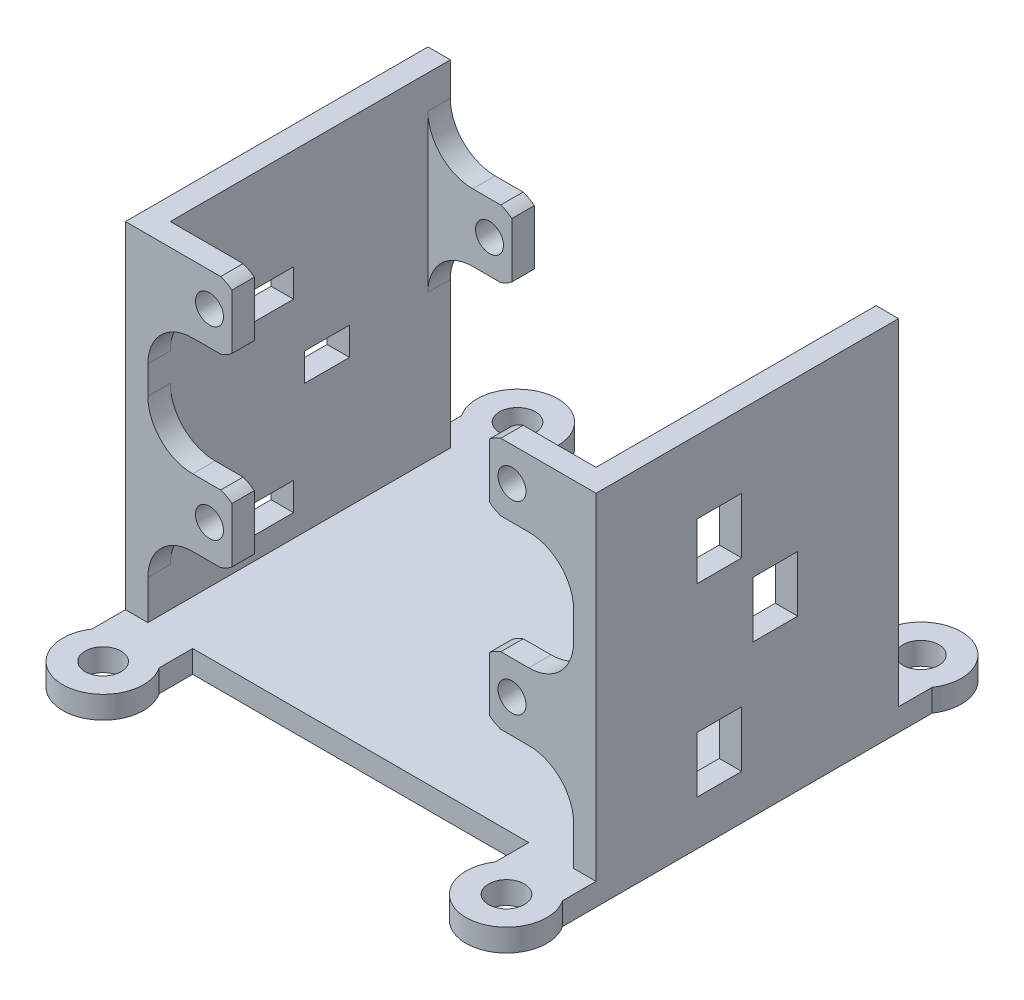
SolidWorks part; units mm, degrees
ref_plane "Спереди" through (0, 0, 0) normal (0, 0, 1) x (1, 0, 0)
ref_plane "Сверху" through (0, 0, 0) normal (0, 1, 0) x (1, 0, 0)
ref_plane "Справа" through (0, 0, 0) normal (1, 0, 0) x (0, 0, -1)
sketch "Эскиз1" plane through (0, 0, 0) normal (0, 1, 0) x (1, 0, 0)
  line L1 (21, -13.5) -> (-21, -13.5)
  line L2 (21, -13.5) -> (21, 13.5)
  line L3 (21, 13.5) -> (-21, 13.5)
  line L4 (-21, -13.5) -> (-21, 13.5)
  line L5 (21, -13.5) -> (-21, 13.5) construction
  line L6 (21, 13.5) -> (-21, -13.5) construction
  point P0 (0, 0)
  dimension "D1" = 42
  dimension "D2" = 27
extrude "Бобышка-Вытянуть1" add sketch "Эскиз1" along normal blind 2
sketch "Эскиз2" plane through (21, 0, 0) normal (1, 0, 0) x (0, 0, -1)
  line L0 (4.5, 2) -> (4.5, 4) construction
  line L1 (-13.5, 2) -> (13.5, 2)
  line L2 (-13.5, 2) -> (-13.5, 32)
  line L3 (-13.5, 32) -> (13.5, 32)
  line L4 (13.5, 2) -> (13.5, 32)
  line L5 (-4.5, 17) -> (-13.5, 17) construction
  line L6 (-4.5, 2) -> (-4.5, 4) construction
  line L7 (-4.5, 4) -> (-13.5, 4) construction
  line L8 (-4.5, 4) -> (-0.5, 4)
  line L9 (-4.5, 4) -> (-4.5, 9)
  line L10 (-4.5, 9) -> (-0.5, 9)
  line L11 (-0.5, 4) -> (-0.5, 9)
  line L12 (0, 32) -> (0, 27.5283) construction
  line L13 (4.5, 4) -> (4.5, 13.5) construction
  line L14 (-4.5, 9) -> (-4.5, 20.5) construction
  line L15 (4.5, 13.5) -> (0.5, 13.5)
  line L16 (4.5, 13.5) -> (4.5, 18.5)
  line L17 (4.5, 18.5) -> (0.5, 18.5)
  line L18 (0.5, 13.5) -> (0.5, 18.5)
  line L20 (-4.5, 20.5) -> (-0.5, 20.5)
  line L21 (-4.5, 20.5) -> (-4.5, 25.5)
  line L22 (-4.5, 25.5) -> (-0.5, 25.5)
  line L23 (-0.5, 20.5) -> (-0.5, 25.5)
  dimension "D1" = 27
  dimension "D2" = 30
  dimension "D3" = 4
  dimension "D4" = 2
  dimension "D5" = 9
  dimension "D6" = 5
  dimension "D7" = 9.5
  dimension "D8" = 4
  dimension "D9" = 5
  dimension "D10" = 11.5
  dimension "D11" = 5
  dimension "D12" = 4
extrude "Бобышка-Вытянуть2" add sketch "Эскиз2" against normal blind 2
mirror "Зеркальное отражение1" about plane through (0, 0, 0) normal (1, 0, 0) of "Бобышка-Вытянуть2"
sketch "Эскиз3" plane through (-21, 0, 0) normal (-1, 0, 0) x (0, 0, 1)
  line L0 (4.5, 25.5) -> (4.5, 20.5) construction
  line L1 (0.5, 25.5) -> (4.5, 25.5)
  line L2 (0.5, 25.5) -> (0.5, 23)
  line L3 (0.5, 23) -> (4.5, 23)
  line L4 (4.5, 25.5) -> (4.5, 23)
  line L5 (-0.5, 18.5) -> (-0.5, 13.5) construction
  line L6 (-4.5, 18.5) -> (-0.5, 18.5)
  line L7 (-4.5, 18.5) -> (-4.5, 16)
  line L8 (-4.5, 16) -> (-0.5, 16)
  line L9 (-0.5, 18.5) -> (-0.5, 16)
  line L10 (4.5, 9) -> (4.5, 4) construction
  line L11 (0.5, 9) -> (4.5, 9)
  line L12 (0.5, 9) -> (0.5, 6.5)
  line L13 (0.5, 6.5) -> (4.5, 6.5)
  line L14 (4.5, 9) -> (4.5, 6.5)
  dimension "D1" = 2.5
  dimension "D2" = 2.5
  dimension "D3" = 2.5
extrude "Бобышка-Вытянуть3" add sketch "Эскиз3" against normal blind 2
sketch "Эскиз4" plane through (0, 0, 13.5) normal (0, 0, -1) x (-1, 0, 0)
  line L0 (-19, 2) -> (-19, 12.5) construction
  line L1 (-19, 2) -> (-19, 32) construction
  line L2 (-19, 12.5) -> (-13.5, 12.5) construction
  line L3 (-19, 9.5) -> (-19, 15.5)
  line L4 (-19, 15.5) -> (-12.5, 15.5)
  line L5 (-19, 9.5) -> (-12.5, 9.5)
  line L6 (-13.5, 12.5) -> (-11.5, 12.5) construction
  line L7 (-11.5, 14.9495) -> (-11.5, 10.0505)
  circle A0 centre (-13.5, 12.5) radius 1.25
  arc A1 (-12.5, 15.5) -> (-11.5, 14.9495) centre (-13.5, 12.5) cw
  arc A2 (-11.5, 10.0505) -> (-12.5, 9.5) centre (-13.5, 12.5) cw
  dimension "D3" = 2.5
  dimension "D1" = 10.5
  dimension "D2" = 5.5
  dimension "D4" = 2
  dimension "D5" = 3
extrude "Бобышка-Вытянуть4" add sketch "Эскиз4" along normal blind 2
mirror "Зеркальное отражение2" about plane through (0, 0, 0) normal (1, 0, 0) of "Бобышка-Вытянуть4"
sketch "Эскиз7" plane through (19, 0, 0) normal (-1, 0, 0) x (0, 0, 1)
  line L0 (13.5, 2) -> (13.5, 12.5) construction
  line L1 (-13.5, 2) -> (-13.5, 22.8) construction
  line L2 (-13.5, 2) -> (-13.5, 32) construction
  line L3 (13.5, 12.5) -> (-13.5, 22.8) construction
  dimension "D1" = 10.5
  dimension "D2" = 20.8
pattern_linear "Линейный массив1" count 2 spacing 16.5 along (0, 1, 0) of "Зеркальное отражение2", "Бобышка-Вытянуть4"
pattern_linear "Линейный массив2" count 2 spacing 26.75 along (0, 0.3564, -0.9343) of "Зеркальное отражение2", "Бобышка-Вытянуть4"
fillet "Скругление1" radius 4 10 edges at (19, 15.5, 12.5) (19, 9.5, 12.5) (-19, 9.5, 12.5) (-19, 15.5, 12.5) (19, 26, 12.5) (-19, 26, 12.5) (-19, 19.0344, -12.4931) (-19, 25.0344, -12.4931) (19, 25.0344, -12.4931) (19, 19.0344, -12.4931)
sketch "Эскиз8" plane through (0, 0, 0) normal (0, 1, 0) x (1, 0, 0)
  line L0 (-21, 13.5) -> (-18, 13.4931)
  line L1 (-15, 13.4931) -> (-19, 13.4931) construction
  line L2 (-18, 13.4931) -> (-18, 18.4931) construction
  line L3 (-21, 13.5) -> (-21, 16.4931)
  line L4 (-15, 13.5) -> (-18, 13.4931)
  line L5 (-15, 13.5) -> (-15, 16.4931)
  circle A0 centre (-18, 18.4931) radius 1.6
  arc A1 (-21, 16.4931) -> (-15, 16.4931) centre (-18, 18.4931) cw
  dimension "D3" = 3.2
  dimension "D1" = 3
  dimension "D2" = 5
extrude "Бобышка-Вытянуть5" add sketch "Эскиз8" along normal blind 2
mirror "Зеркальное отражение3" about plane through (0, 0, 0) normal (1, 0, 0) of "Бобышка-Вытянуть5"
mirror "Зеркальное отражение4" about plane through (0, 0, 0) normal (0, 0, 1) of "Зеркальное отражение3", "Бобышка-Вытянуть5"
